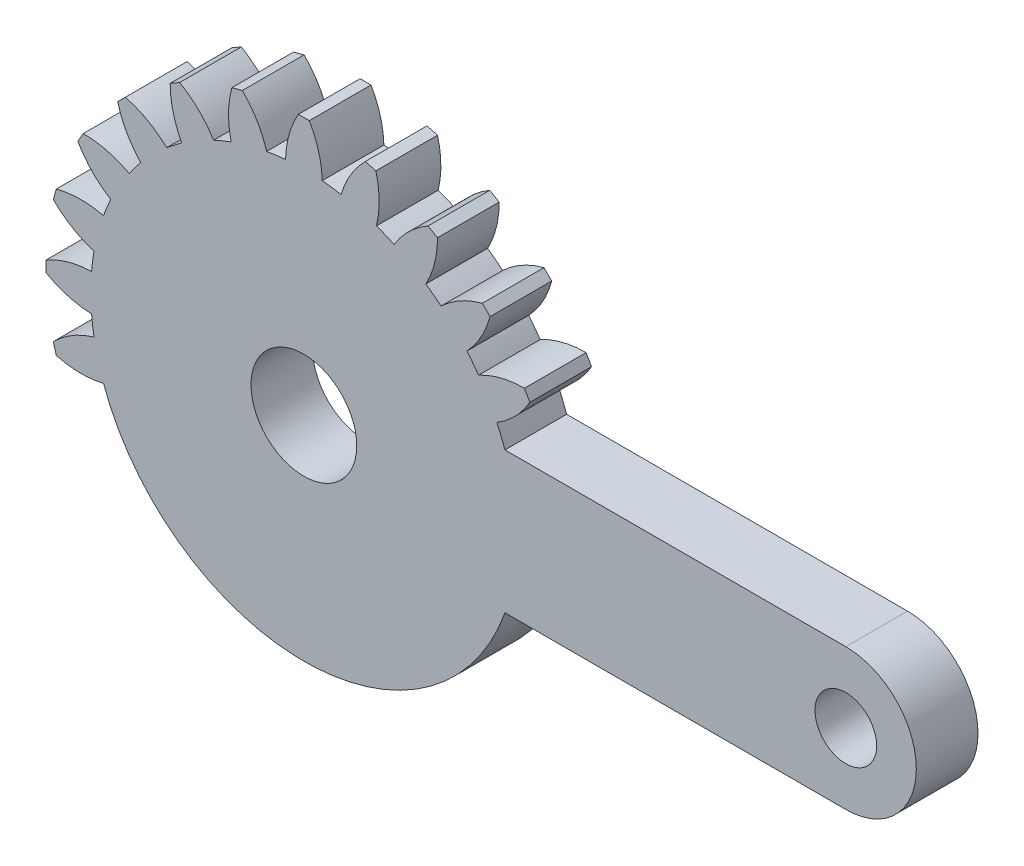
SolidWorks part; units mm, degrees
ref_plane "Front Plane" through (0, 0, 0) normal (0, 0, 1) x (1, 0, 0)
ref_plane "Top Plane" through (0, 0, 0) normal (0, 1, 0) x (1, 0, 0)
ref_plane "Right Plane" through (0, 0, 0) normal (1, 0, 0) x (0, 0, -1)
sketch "Sketch1" plane through (0, 0, 0) normal (0, 0, 1) x (1, 0, 0)
  line L0 (0, 0) -> (30.75, 0) construction
  line L1 (0, -14.63) -> (0, 14.63) construction
  line L2 (-0.31, 14.63) -> (0.31, 14.63)
  line L3 (3.4871, 14.2117) -> (4.086, 14.0513)
  line L4 (7.0465, 12.825) -> (7.5835, 12.515)
  line L5 (10.1258, 10.5642) -> (10.5642, 10.1258)
  line L6 (12.515, 7.5835) -> (12.825, 7.0465)
  line L7 (14.0513, 4.086) -> (14.2117, 3.4871)
  line L8 (14.63, 0.31) -> (14.63, -0.31)
  line L9 (14.2117, -3.4871) -> (14.0513, -4.086)
  line L10 (12.825, -7.0465) -> (12.515, -7.5835)
  line L11 (10.5642, -10.1258) -> (10.1258, -10.5642)
  line L12 (7.5835, -12.515) -> (7.0465, -12.825)
  line L13 (4.086, -14.0513) -> (3.4871, -14.2117)
  line L14 (0.31, -14.63) -> (-0.31, -14.63)
  line L15 (-3.4871, -14.2117) -> (-4.086, -14.0513)
  line L16 (-7.0465, -12.825) -> (-7.5835, -12.515)
  line L17 (-10.1258, -10.5642) -> (-10.5642, -10.1258)
  line L18 (-12.515, -7.5835) -> (-12.825, -7.0465)
  line L19 (-14.0513, -4.086) -> (-14.2117, -3.4871)
  line L20 (-14.63, -0.31) -> (-14.63, 0.31)
  line L21 (-14.2117, 3.4871) -> (-14.0513, 4.086)
  line L22 (-12.825, 7.0465) -> (-12.515, 7.5835)
  line L23 (-10.5642, 10.1258) -> (-10.1258, 10.5642)
  line L24 (-7.5835, 12.515) -> (-7.0465, 12.825)
  line L25 (-4.086, 14.0513) -> (-3.4871, 14.2117)
  line L26 (30.75, -4) -> (30.75, 4)
  line L27 (30.75, 4) -> (11.4091, 4)
  line L28 (30.75, -4) -> (11.4091, -4)
  circle A0 centre (0, 0) radius 1.75
  circle A1 centre (30.75, 0) radius 1.75
  circle A2 centre (0, 0) radius 12.09
  arc A3 (-1.04, 12.0452) -> (-0.31, 14.63) centre (4.3585, 11.9161) cw
  arc A4 (1.04, 12.0452) -> (0.31, 14.63) centre (-4.3585, 11.9161) ccw
  arc A5 (2.113, 11.9039) -> (3.4871, 14.2117) centre (7.294, 10.382) cw
  arc A6 (4.1221, 11.3656) -> (4.086, 14.0513) centre (-1.1258, 12.6381) ccw
  arc A7 (5.1219, 10.9514) -> (7.0465, 12.825) centre (9.7326, 8.1404) cw
  arc A8 (6.9233, 9.9114) -> (7.5835, 12.515) centre (2.1835, 12.4988) ccw
  arc A9 (7.7818, 9.2526) -> (10.1258, 10.5642) centre (11.5078, 5.344) cw
  arc A10 (9.2526, 7.7818) -> (10.5642, 10.1258) centre (5.344, 11.5078) ccw
  arc A11 (9.9114, 6.9233) -> (12.515, 7.5835) centre (12.4988, 2.1835) cw
  arc A12 (10.9514, 5.1219) -> (12.825, 7.0465) centre (8.1404, 9.7326) ccw
  arc A13 (11.3656, 4.1221) -> (14.0513, 4.086) centre (12.6381, -1.1258) cw
  arc A14 (11.9039, 2.113) -> (14.2117, 3.4871) centre (10.382, 7.294) ccw
  arc A15 (12.0452, 1.04) -> (14.63, 0.31) centre (11.9161, -4.3585) cw
  arc A16 (12.0452, -1.04) -> (14.63, -0.31) centre (11.9161, 4.3585) ccw
  arc A17 (11.9039, -2.113) -> (14.2117, -3.4871) centre (10.382, -7.294) cw
  arc A18 (11.3656, -4.1221) -> (14.0513, -4.086) centre (12.6381, 1.1258) ccw
  arc A19 (10.9514, -5.1219) -> (12.825, -7.0465) centre (8.1404, -9.7326) cw
  arc A20 (9.9114, -6.9233) -> (12.515, -7.5835) centre (12.4988, -2.1835) ccw
  arc A21 (9.2526, -7.7818) -> (10.5642, -10.1258) centre (5.344, -11.5078) cw
  arc A22 (7.7818, -9.2526) -> (10.1258, -10.5642) centre (11.5078, -5.344) ccw
  arc A23 (6.9233, -9.9114) -> (7.5835, -12.515) centre (2.1835, -12.4988) cw
  arc A24 (5.1219, -10.9514) -> (7.0465, -12.825) centre (9.7326, -8.1404) ccw
  arc A25 (4.1221, -11.3656) -> (4.086, -14.0513) centre (-1.1258, -12.6381) cw
  arc A26 (2.113, -11.9039) -> (3.4871, -14.2117) centre (7.294, -10.382) ccw
  arc A27 (1.04, -12.0452) -> (0.31, -14.63) centre (-4.3585, -11.9161) cw
  arc A28 (-1.04, -12.0452) -> (-0.31, -14.63) centre (4.3585, -11.9161) ccw
  arc A29 (-2.113, -11.9039) -> (-3.4871, -14.2117) centre (-7.294, -10.382) cw
  arc A30 (-4.1221, -11.3656) -> (-4.086, -14.0513) centre (1.1258, -12.6381) ccw
  arc A31 (-5.1219, -10.9514) -> (-7.0465, -12.825) centre (-9.7326, -8.1404) cw
  arc A32 (-6.9233, -9.9114) -> (-7.5835, -12.515) centre (-2.1835, -12.4988) ccw
  arc A33 (-7.7818, -9.2526) -> (-10.1258, -10.5642) centre (-11.5078, -5.344) cw
  arc A34 (-9.2526, -7.7818) -> (-10.5642, -10.1258) centre (-5.344, -11.5078) ccw
  arc A35 (-9.9114, -6.9233) -> (-12.515, -7.5835) centre (-12.4988, -2.1835) cw
  arc A36 (-10.9514, -5.1219) -> (-12.825, -7.0465) centre (-8.1404, -9.7326) ccw
  arc A37 (-11.3656, -4.1221) -> (-14.0513, -4.086) centre (-12.6381, 1.1258) cw
  arc A38 (-11.9039, -2.113) -> (-14.2117, -3.4871) centre (-10.382, -7.294) ccw
  arc A39 (-12.0452, -1.04) -> (-14.63, -0.31) centre (-11.9161, 4.3585) cw
  arc A40 (-12.0452, 1.04) -> (-14.63, 0.31) centre (-11.9161, -4.3585) ccw
  arc A41 (-11.9039, 2.113) -> (-14.2117, 3.4871) centre (-10.382, 7.294) cw
  arc A42 (-11.3656, 4.1221) -> (-14.0513, 4.086) centre (-12.6381, -1.1258) ccw
  arc A43 (-10.9514, 5.1219) -> (-12.825, 7.0465) centre (-8.1404, 9.7326) cw
  arc A44 (-9.9114, 6.9233) -> (-12.515, 7.5835) centre (-12.4988, 2.1835) ccw
  arc A45 (-9.2526, 7.7818) -> (-10.5642, 10.1258) centre (-5.344, 11.5078) cw
  arc A46 (-7.7818, 9.2526) -> (-10.1258, 10.5642) centre (-11.5078, 5.344) ccw
  arc A47 (-6.9233, 9.9114) -> (-7.5835, 12.515) centre (-2.1835, 12.4988) cw
  arc A48 (-5.1219, 10.9514) -> (-7.0465, 12.825) centre (-9.7326, 8.1404) ccw
  arc A49 (-4.1221, 11.3656) -> (-4.086, 14.0513) centre (1.1258, 12.6381) cw
  arc A50 (-2.113, 11.9039) -> (-3.4871, 14.2117) centre (-7.294, 10.382) ccw
  arc A51 (30.75, -4) -> (30.75, 4) centre (30.75, 0) ccw
  point P9 (0, 0)
  point P157 (30.75, 0)
  dimension "D2" = 3.5
  dimension "D3" = 3.5
  dimension "D4" = 24.18
  dimension "D6" = 5.4
  dimension "D10" = 8
  dimension "D1" = 30.75
  dimension "D5" = 29.26
  dimension "D7" = 0.31
  dimension "D8" = 1.04
  dimension "D9" = 24
extrude "Boss-Extrude1" add sketch "Sketch1" along normal blind 3.5 contours L26 A51 A1 | A2 A38 L19 A37 | A2 A40 L20 A39 | A2 A42 L21 A41 | A2 A44 L22 A43 | A2 A46 L23 A45 | A2 A48 L24 A47 | A2 A50 L25 A49 | A2 A4 L2 A3 | A2 A6 L3 A5 | A2 A8 L4 A7 | A2 A10 L5 A9 | A2 A12 L6 A11 | A2 A14 L7 L27 | A2 A16 L8 A15 | A17 A2 L28 L9 | A2 A17 L9 L28 L26 A1 L27 L7 A14 A15 L8 A16 | A2 A39 | A0
sketch "Sketch2" plane through (0, 0, 3.5) normal (0, 0, 1) x (1, 0, 0)
  circle A1 centre (0, 0) radius 3
  point P6 (0, 0)
  dimension "D3" = 6
extrude "Cut-Extrude1" cut sketch "Sketch2" against normal through all
